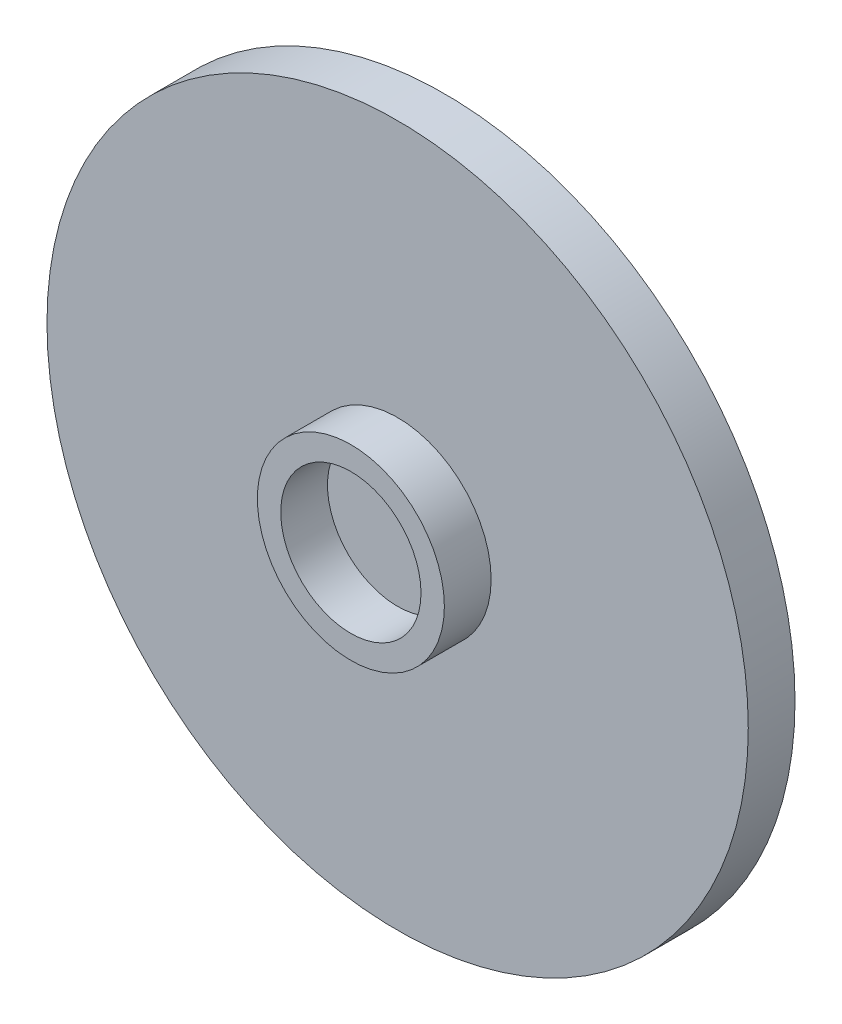
SolidWorks part; units mm, degrees
ref_plane "Front Plane" through (0, 0, 0) normal (0, 0, 1) x (1, 0, 0)
ref_plane "Top Plane" through (0, 0, 0) normal (0, 1, 0) x (1, 0, 0)
ref_plane "Right Plane" through (0, 0, 0) normal (1, 0, 0) x (0, 0, -1)
sketch "Sketch1" plane through (0, 0, 0) normal (0, 0, 1) x (1, 0, 0)
  circle A0 centre (0, 0) radius 11.9062
  dimension "D1" = 23.8125
extrude "Boss-Extrude1" add sketch "Sketch1" along normal blind 1.5875
sketch "Sketch2" plane through (0, 0, 1.5875) normal (0, 0, 1) x (1, 0, 0)
  circle A0 centre (0, 0) radius 3.175
  circle A1 centre (0, 0) radius 2.3813
  dimension "D1" = 6.35
  dimension "D2" = 4.7625
extrude "Boss-Extrude2" add sketch "Sketch2" along normal blind 1.5875
